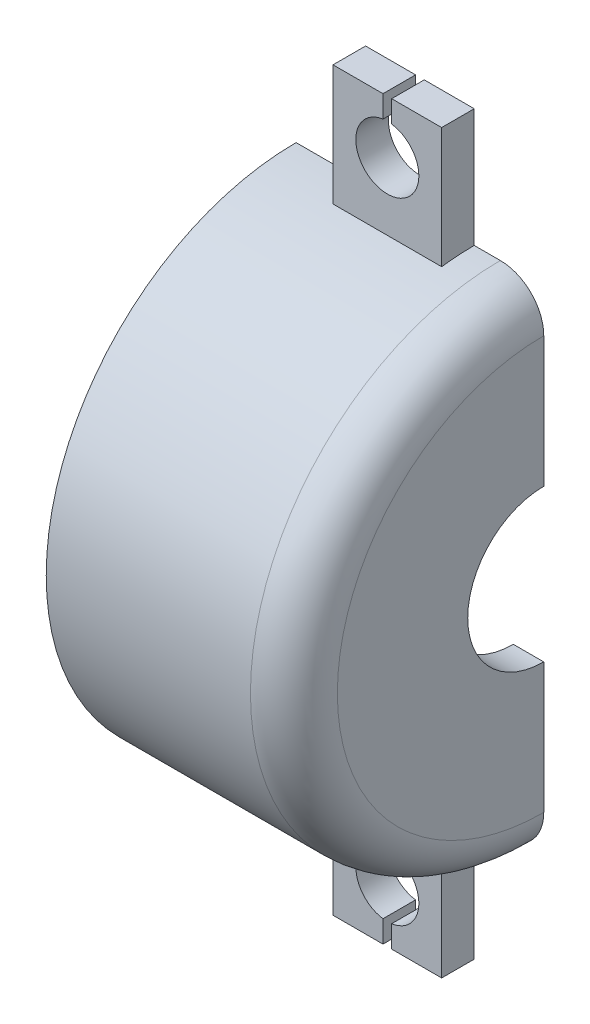
SolidWorks part; units mm, degrees
ref_plane "前视基准面" through (0, 0, 0) normal (0, 0, 1) x (1, 0, 0)
ref_plane "上视基准面" through (0, 0, 0) normal (0, 1, 0) x (1, 0, 0)
ref_plane "右视基准面" through (0, 0, 0) normal (1, 0, 0) x (0, 0, -1)
sketch "草图1" plane through (0, 0, 0) normal (0, 0, 1) x (1, 0, 0)
  line L0 (-19.1835, 2.5) -> (0.9247, 2.5) construction
  line L1 (-11.6, 6) -> (-11.6, 14)
  line L2 (-11.6, 14) -> (-23, 14)
  line L3 (-13, 6) -> (-13, 7.4)
  line L4 (-13, 7.4) -> (-17, 7.4)
  line L5 (-17, 7.4) -> (-17, 11)
  line L6 (-17, 11) -> (-20, 11)
  line L7 (-20, 11) -> (-20, 13)
  line L8 (-13, 6) -> (-11.6, 6)
  line L9 (-23, 12) -> (-20, 13)
  line L12 (-23, 12) -> (-23, 14)
  dimension "D1" = 8
  dimension "D2" = 4
  dimension "D3" = 3
  dimension "D4" = 2
  dimension "D5" = 2
  dimension "D6" = 1.4
  dimension "D7" = 3
  dimension "D8" = 1
  dimension "D9" = 8.5
revolve "旋转1" add sketch "草图1" angle 360 about L0
sketch "草图3" plane through (0, 0, 0) normal (0, 0, 1) x (1, 0, 0)
  line L1 (-24.3637, 14.781) -> (-9.614, 14.781)
  line L2 (-24.3637, 14.781) -> (-24.3637, -10.1752)
  line L3 (-24.3637, -10.1752) -> (-9.614, -10.1752)
  line L4 (-9.614, 14.781) -> (-9.614, -10.1752)
extrude "切除-拉伸2" cut sketch "草图3" against normal blind 18
sketch "草图4" plane through (0, 0, 0) normal (0, 0, -1) x (-1, 0, 0)
  line L0 (9.2523, 2.5) -> (26.9967, 2.5) construction
  line L2 (17.3, -11.725) -> (17.3, -9) construction
  line L3 (17.3, 21.6797) -> (17.3, 18.45) construction
  line L4 (14.8, 14) -> (14.8, 19.45)
  line L5 (14.8, -14.45) -> (19.8, -9) construction
  line L6 (14.8, 19.45) -> (17.1, 19.45)
  line L7 (19.8, 14) -> (19.8, 19.45)
  line L8 (14.8, 14) -> (19.8, 19.45) construction
  line L9 (14.8, 19.45) -> (19.8, 14) construction
  line L10 (17.5, 19.45) -> (17.5, 18.4361)
  line L11 (17.1, 19.45) -> (17.1, 18.4361)
  line L12 (17.5, 19.45) -> (19.8, 19.45)
  line L13 (17.3, 16.725) -> (17.3, 14) construction
  line L14 (14.8, -9) -> (19.8, -14.45) construction
  line L15 (17.3, -16.6797) -> (17.3, -13.45) construction
  line L16 (14.8, 14) -> (14.8, 12.6694)
  line L17 (14.8, 12.6694) -> (19.8, 12.6694)
  line L18 (19.8, 14) -> (19.8, 12.6694)
  line L19 (19.8, -9) -> (19.8, -7.6694)
  line L20 (14.8, -7.6694) -> (19.8, -7.6694)
  line L21 (14.8, -9) -> (14.8, -7.6694)
  line L22 (17.5, -14.45) -> (19.8, -14.45)
  line L23 (17.1, -14.45) -> (17.1, -13.4361)
  line L24 (17.5, -14.45) -> (17.5, -13.4361)
  line L25 (19.8, -9) -> (19.8, -14.45)
  line L26 (14.8, -14.45) -> (17.1, -14.45)
  line L27 (14.8, -9) -> (14.8, -14.45)
  arc A0 (17.1, 18.4361) -> (17.5, 18.4361) centre (17.3, 17) ccw
  arc A1 (17.1, -13.4361) -> (17.5, -13.4361) centre (17.3, -12) cw
  point P9 (17.3, 16.725)
  dimension "D1" = 2.9
  dimension "D3" = 1
  dimension "D4" = 5
  dimension "D5" = 0.2
extrude "凸台-拉伸2" add sketch "草图4" against normal blind 1.5
fillet "圆角1" radius 2 1 edges at (-11.6, 2.5, 11.5)
